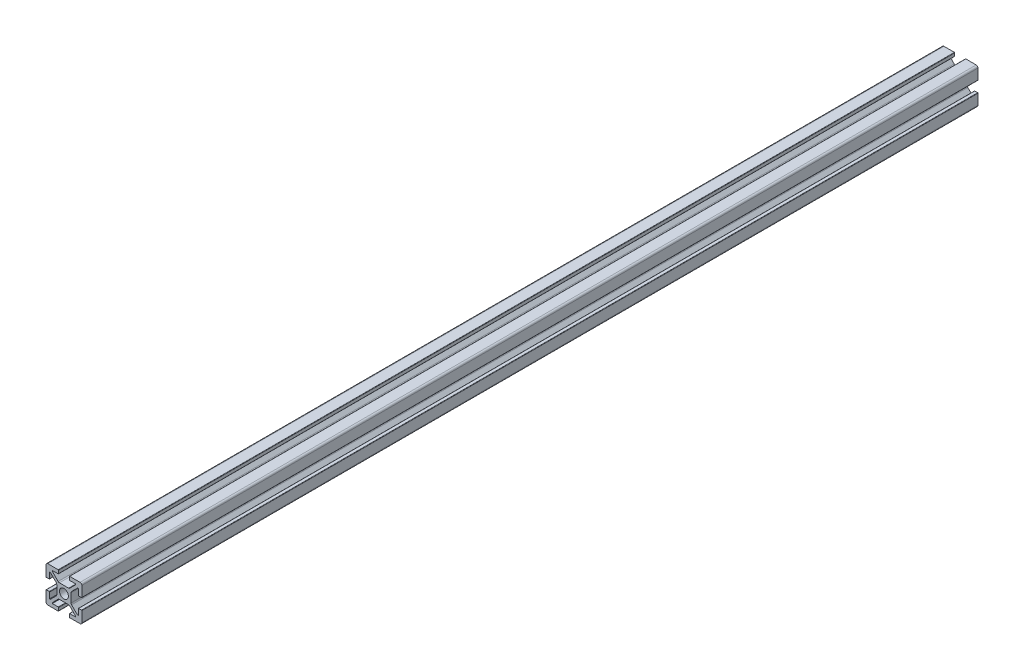
SolidWorks part; units mm, degrees
ref_plane "Front Plane" through (0, 0, 0) normal (0, 0, 1) x (1, 0, 0)
ref_plane "Top Plane" through (0, 0, 0) normal (0, 1, 0) x (1, 0, 0)
ref_plane "Right Plane" through (0, 0, 0) normal (1, 0, 0) x (0, 0, -1)
sketch "Sketch1" plane through (0, 0, 0) normal (0, 0, 1) x (1, 0, 0)
  line L0 (0.2, 13) -> (1.8, 13)
  line L1 (13.2, 0) -> (19, 0)
  line L2 (0, 13.2) -> (0, 19)
  line L3 (1, 20) -> (6.8, 20)
  line L4 (20, 1) -> (20, 6.8)
  line L5 (2, 13.2) -> (2, 16.5)
  line L6 (2, 16.5) -> (2.4393, 16.5)
  line L7 (2.4393, 16.5) -> (5.7071, 13.2322)
  line L8 (6, 12.5251) -> (6, 7.4749)
  line L11 (7.4749, 14) -> (10, 14)
  line L12 (3.5, 17.5607) -> (6.7678, 14.2929)
  line L13 (3.5, 18) -> (3.5, 17.5607)
  line L14 (6.8, 18) -> (3.5, 18)
  line L15 (6.8, 20) -> (1, 20)
  line L16 (7, 19.8) -> (7, 18.2)
  line L17 (19.8, 7) -> (18.2, 7)
  line L18 (20, 6.8) -> (20, 1)
  line L19 (18, 6.8) -> (18, 3.5)
  line L20 (18, 3.5) -> (17.5607, 3.5)
  line L21 (17.5607, 3.5) -> (14.2929, 6.7678)
  line L22 (14, 7.4749) -> (14, 12.5251)
  line L23 (12.5251, 6) -> (10, 6)
  line L24 (16.5, 2.4393) -> (13.2322, 5.7071)
  line L25 (16.5, 2) -> (16.5, 2.4393)
  line L26 (13.2, 2) -> (16.5, 2)
  line L27 (13.2, 0) -> (19, 0)
  line L28 (13, 0.2) -> (13, 1.8)
  line L30 (13, 19.8) -> (13, 18.2)
  line L31 (13.2, 20) -> (19, 20)
  line L32 (13.2, 18) -> (16.5, 18)
  line L33 (16.5, 18) -> (16.5, 17.5607)
  line L34 (16.5, 17.5607) -> (13.2322, 14.2929)
  line L35 (12.5251, 14) -> (10, 14)
  line L36 (17.5607, 16.5) -> (14.2929, 13.2322)
  line L37 (18, 16.5) -> (17.5607, 16.5)
  line L38 (18, 13.2) -> (18, 16.5)
  line L39 (20, 13.2) -> (20, 19)
  line L40 (19.8, 13) -> (18.2, 13)
  line L41 (7, 0.2) -> (7, 1.8)
  line L42 (6.8, 0) -> (1, 0)
  line L43 (6.8, 2) -> (3.5, 2)
  line L44 (3.5, 2) -> (3.5, 2.4393)
  line L45 (3.5, 2.4393) -> (6.7678, 5.7071)
  line L46 (7.4749, 6) -> (10, 6)
  line L47 (2.4393, 3.5) -> (5.7071, 6.7678)
  line L48 (2, 3.5) -> (2.4393, 3.5)
  line L49 (2, 6.8) -> (2, 3.5)
  line L50 (20, 19) -> (20, 13.2)
  line L51 (1, 0) -> (6.8, 0)
  line L52 (0, 6.8) -> (0, 1)
  line L53 (13.2, 20) -> (19, 20)
  line L54 (0.2, 7) -> (1.8, 7)
  arc A0 (20, 1) -> (19, 0) centre (19, 1) cw
  arc A1 (1, 0) -> (0, 1) centre (1, 1) cw
  arc A2 (0, 19) -> (1, 20) centre (1, 19) cw
  arc A3 (20, 19) -> (19, 20) centre (19, 19) ccw
  arc A4 (14.2929, 6.7678) -> (14, 7.4749) centre (15, 7.4749) cw
  arc A5 (12.5251, 6) -> (13.2322, 5.7071) centre (12.5251, 5) cw
  arc A6 (6.7678, 5.7071) -> (7.4749, 6) centre (7.4749, 5) cw
  arc A7 (5.7071, 6.7678) -> (6, 7.4749) centre (5, 7.4749) ccw
  arc A8 (14.2929, 13.2322) -> (14, 12.5251) centre (15, 12.5251) ccw
  arc A9 (13.2322, 14.2929) -> (12.5251, 14) centre (12.5251, 15) cw
  arc A10 (6, 12.5251) -> (5.7071, 13.2322) centre (5, 12.5251) ccw
  arc A11 (7.4749, 14) -> (6.7678, 14.2929) centre (7.4749, 15) cw
  arc A12 (0, 6.8) -> (0.2, 7) centre (0.2, 6.8) cw
  arc A13 (2, 6.8) -> (1.8, 7) centre (1.8, 6.8) ccw
  arc A14 (7, 1.8) -> (6.8, 2) centre (6.8, 1.8) ccw
  arc A15 (7, 0.2) -> (6.8, 0) centre (6.8, 0.2) cw
  arc A16 (13.2, 0) -> (13, 0.2) centre (13.2, 0.2) cw
  arc A17 (13.2, 2) -> (13, 1.8) centre (13.2, 1.8) ccw
  arc A18 (18.2, 7) -> (18, 6.8) centre (18.2, 6.8) ccw
  arc A19 (19.8, 7) -> (20, 6.8) centre (19.8, 6.8) cw
  arc A20 (20, 13.2) -> (19.8, 13) centre (19.8, 13.2) cw
  arc A21 (18, 13.2) -> (18.2, 13) centre (18.2, 13.2) ccw
  arc A22 (13, 19.8) -> (13.2, 20) centre (13.2, 19.8) cw
  arc A23 (13, 18.2) -> (13.2, 18) centre (13.2, 18.2) ccw
  arc A24 (6.8, 18) -> (7, 18.2) centre (6.8, 18.2) ccw
  arc A25 (7, 19.8) -> (6.8, 20) centre (6.8, 19.8) ccw
  arc A26 (1.8, 13) -> (2, 13.2) centre (1.8, 13.2) ccw
  arc A27 (0.2, 13) -> (0, 13.2) centre (0.2, 13.2) cw
  circle A28 centre (10, 10) radius 2.5
  point P19 (2, 13)
  dimension "D1" = 1
  dimension "D4" = 1
  dimension "D5" = 0.2
  dimension "D6" = 0.2
  dimension "D7" = 5
  dimension "D2" = 7
  dimension "D3" = 2
  dimension "D9" = 3.5
extrude "Boss-Extrude1" add sketch "Sketch1" along normal blind 500 contours A27 L0 A26 L5 L6 L7 A10 L8 A7 L47 L48 L49 A13 L54 A12 L52 A1 L42 A15 L41 A14 L43 L44 L45 A6 L46 L23 A5 L24 L25 L26 A17 L28 A16 L1 A0 L4 A19 L17 A18 L19 L20 L21 A4 L22 A8 L36 L37 L38 A21 L40
